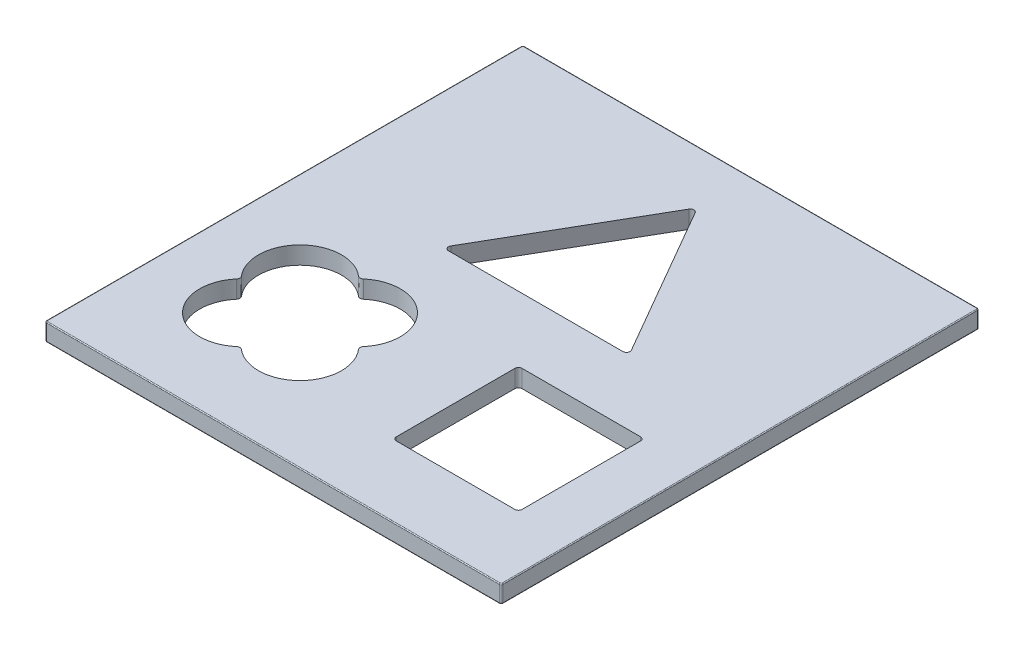
SolidWorks part; units mm, degrees
ref_plane "Front Plane" through (0, 0, 0) normal (0, 0, 1) x (1, 0, 0)
ref_plane "Top Plane" through (0, 0, 0) normal (0, 1, 0) x (1, 0, 0)
ref_plane "Right Plane" through (0, 0, 0) normal (1, 0, 0) x (0, 0, -1)
sketch "Sketch1" plane through (0, 0, 0) normal (0, 1, 0) x (1, 0, 0)
  line L0 (0, 0) -> (0, 83.2739) construction
  line L1 (-63, 66.5) -> (63, 66.5)
  line L2 (-63.5, 66) -> (-63.5, -66)
  line L3 (-63, -66.5) -> (63, -66.5)
  line L4 (63.5, 66) -> (63.5, -66)
  line L5 (0, 0) -> (141.3576, 0) construction
  arc A0 (-63.5, -66) -> (-63, -66.5) centre (-63, -66) ccw
  arc A1 (63, -66.5) -> (63.5, -66) centre (63, -66) ccw
  arc A2 (63, 66.5) -> (63.5, 66) centre (63, 66) cw
  arc A3 (-63, 66.5) -> (-63.5, 66) centre (-63, 66) ccw
  point P12 (63.5, -66.5)
  point P15 (63.5, 66.5)
  point P18 (-63.5, 66.5)
  dimension "D3" = 0.5
  dimension "D1" = 127
  dimension "D2" = 133
extrude "Boss-Extrude2" add sketch "Sketch1" along normal blind 4.9 contours L2 A0 L3 A1 L4 A2 L1 A3
fillet "Fillet2" radius 0.25 16 edges at (-63.5, 0, 0) (-63.3536, 0, 66.3536) (0, 0, 66.5) (63.3536, 0, 66.3536) (63.5, 0, 0) (63.3536, 0, -66.3536) (0, 0, -66.5) (-63.3536, 0, -66.3536) (0, 4.9, -66.5) (63.3536, 4.9, -66.3536) (63.5, 4.9, 0) (63.3536, 4.9, 66.3536) (0, 4.9, 66.5) (-63.3536, 4.9, 66.3536) (-63.5, 4.9, 0) (-63.3536, 4.9, -66.3536)
sketch "Sketch3" plane through (0, 4.9, 0) normal (0, 1, 0) x (1, 0, 0)
  line L0 (0, 0) -> (95.6361, 0) construction
  line L1 (0, 0) -> (0, 70.8636) construction
  line L2 (-63, 66.5) -> (63, 66.5) construction
  line L3 (-0.866, 50.12) -> (-25.134, 8.0867)
  line L4 (-24.2679, 6.5867) -> (24.2679, 6.5867)
  line L5 (25.134, 8.0867) -> (0.866, 50.12)
  line L6 (-63.5, -66) -> (-63.5, 66) construction
  line L7 (0, 0) -> (-83.4881, 0) construction
  line L8 (0, 0) -> (0, -71.8164) construction
  line L9 (63.5, 66) -> (63.5, -66) construction
  line L10 (14.3, -11.5) -> (47.3, -11.5)
  line L11 (13.3, -12.5) -> (13.3, -45.5)
  line L12 (14.3, -46.5) -> (47.3, -46.5)
  line L13 (48.3, -12.5) -> (48.3, -45.5)
  line L14 (63, -66.5) -> (-63, -66.5) construction
  line L15 (-30.01, -2.9611) -> (-30.01, -56.1732) construction
  line L20 (-73.2456, -29) -> (88.252, -29) construction
  line L21 (-30.01, -12.64) -> (-46.37, -29) construction
  line L30 (-46.37, -29) -> (-30.01, -45.36) construction
  line L31 (-30.01, -45.36) -> (-13.65, -29) construction
  line L32 (-13.65, -29) -> (-30.01, -12.64) construction
  line L33 (-30.01, 3.72) -> (-62.73, -29) construction
  line L34 (-62.73, -29) -> (-30.01, -61.72) construction
  line L35 (-30.01, -61.72) -> (2.71, -29) construction
  line L36 (2.71, -29) -> (-30.01, 3.72) construction
  circle A0 centre (0, 21.5978) radius 15.0111 construction
  circle A6 centre (-30.01, -29) radius 11.5683 construction
  circle A8 centre (-30.01, -29) radius 23.1365 construction
  arc A9 (-13.0473, -28.3492) -> (-29.3592, -12.0373) centre (-21.83, -20.82) ccw
  arc A10 (-13.0473, -29.6508) -> (-29.3592, -45.9627) centre (-21.83, -37.18) cw
  arc A11 (-30.6608, -45.9627) -> (-46.9727, -29.6508) centre (-38.19, -37.18) cw
  arc A12 (-46.9727, -28.3492) -> (-30.6608, -12.0373) centre (-38.19, -20.82) cw
  arc A13 (24.2679, 6.5867) -> (25.134, 8.0867) centre (24.2679, 7.5867) ccw
  arc A14 (-25.134, 8.0867) -> (-24.2679, 6.5867) centre (-24.2679, 7.5867) ccw
  arc A15 (-0.866, 50.12) -> (0.866, 50.12) centre (0, 49.62) cw
  arc A16 (13.3, -45.5) -> (14.3, -46.5) centre (14.3, -45.5) ccw
  arc A17 (47.3, -46.5) -> (48.3, -45.5) centre (47.3, -45.5) ccw
  arc A18 (47.3, -11.5) -> (48.3, -12.5) centre (47.3, -12.5) cw
  arc A19 (14.3, -11.5) -> (13.3, -12.5) centre (14.3, -12.5) ccw
  arc A20 (-46.9727, -29.6508) -> (-46.9727, -28.3492) centre (-47.732, -29) ccw
  arc A21 (-29.3592, -45.9627) -> (-30.6608, -45.9627) centre (-30.01, -46.722) ccw
  arc A22 (-13.0473, -28.3492) -> (-13.0473, -29.6508) centre (-12.288, -29) ccw
  arc A23 (-29.3592, -12.0373) -> (-30.6608, -12.0373) centre (-30.01, -11.278) cw
  point P48 (-26, 6.5867)
  point P51 (0, 51.62)
  point P58 (48.3, -11.5)
  point P61 (13.3, -11.5)
  dimension "D8" = 1
  dimension "D6" = 26.95
  dimension "D9" = 1
  dimension "D10" = 1
  dimension "D1" = 14.88
  dimension "D2" = 37.5
  dimension "D3" = 15.2
  dimension "D4" = 20
  dimension "D5" = 35
  dimension "D7" = 21.14
extrude "Cut-Extrude1" cut sketch "Sketch3" against normal through all
